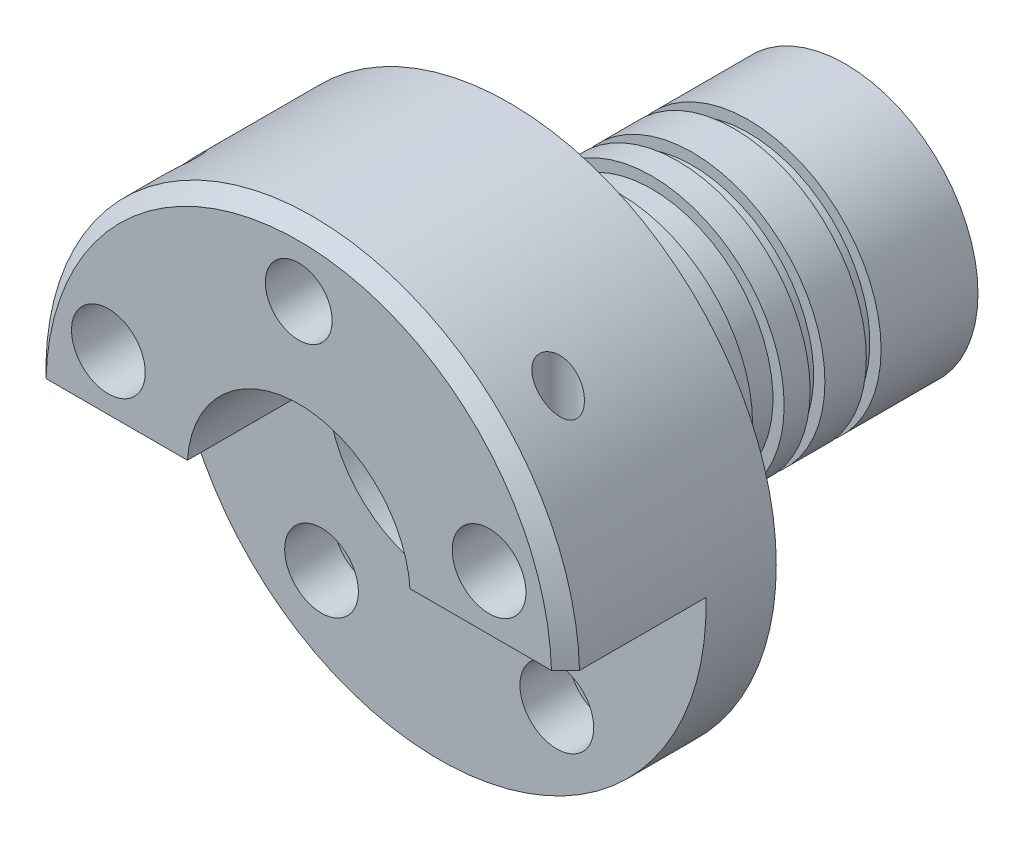
SolidWorks part; units mm, degrees
ref_plane "Front Plane" through (0, 0, 0) normal (0, 0, 1) x (1, 0, 0)
ref_plane "Top Plane" through (0, 0, 0) normal (0, 1, 0) x (1, 0, 0)
ref_plane "Right Plane" through (0, 0, 0) normal (1, 0, 0) x (0, 0, -1)
sketch "Sketch1" plane through (0, 0, 0) normal (0, 0, 1) x (1, 0, 0)
  circle A0 centre (0, 0) radius 15.875
  circle A1 centre (0, 0) radius 18.875
  dimension "D1" = 31.75
  dimension "D2" = 37.75
extrude "Boss-Extrude1" add sketch "Sketch1" along normal blind 47.85
sketch "Sketch2" plane through (0, 0, 47.85) normal (0, 0, 1) x (1, 0, 0)
  circle A0 centre (0, 0) radius 38
  dimension "D1" = 76
extrude "Boss-Extrude2" add sketch "Sketch2" along normal blind 30
sketch "Sketch3" plane through (0, 0, 47.85) normal (0, 0, -1) x (-1, 0, 0)
  circle A0 centre (0, 0) radius 15.875
  circle A1 centre (0, 0) radius 15.875 construction
extrude "Cut-Extrude1" cut sketch "Sketch3" against normal blind 47.85
sketch "Sketch4" plane through (0, 0, 0) normal (0, 1, 0) x (1, 0, 0)
  line L0 (-38, -57.85) -> (38, -57.85) construction
  line L1 (-38, -47.85) -> (-38, -77.85) construction
  line L2 (38, -77.85) -> (38, -47.85) construction
  line L3 (38, -47.85) -> (-38, -47.85) construction
  line L4 (-38, -77.85) -> (38, -77.85) construction
  line L5 (-38, -57.85) -> (38, -57.85)
  line L6 (-38, -57.85) -> (-38, -77.85)
  line L7 (-38, -77.85) -> (38, -77.85)
  line L8 (38, -57.85) -> (38, -77.85)
  dimension "D1" = 10
extrude "Cut-Extrude2" cut sketch "Sketch4" against normal blind 47.85
sketch "Sketch5" plane through (0, 0, 0) normal (0, -1, 0) x (-1, 0, 0)
  line L0 (38, -77.85) -> (15.875, -57.85) construction
  line L1 (-15.875, -77.85) -> (-38, -57.85) construction
  circle A0 centre (26.9375, -67.85) radius 2.65
  circle A1 centre (-26.9375, -67.85) radius 2.65
  dimension "D1" = 5.3
  dimension "D2" = 5.3
extrude "Cut-Extrude3" cut sketch "Sketch5" against normal blind 47.85
sketch "Sketch11" plane through (0, 0, 77.85) normal (0, 0, 1) x (1, 0, 0)
  line L0 (0, 0) -> (0, 38) construction
  arc A0 (38, 0) -> (-38, 0) centre (0, 0) ccw construction
  circle A1 centre (0, 0) radius 28.5 construction
  circle A2 centre (0, 28.5) radius 1
  point P19 (0, 0)
  dimension "D1" = 57
  dimension "D2" = 2
extrude "Cut-Extrude4" cut sketch "Sketch11" against normal up to surface (30 mm away) up to face at (18.875, 0, 47.85)
sketch "Sketch12" plane through (0, 0, 77.85) normal (0, 0, 1) x (1, 0, 0)
  circle A0 centre (0, 28.5) radius 4.7625
  point P16 (0, 0)
  dimension "D1" = 9.525
extrude "Cut-Extrude5" cut sketch "Sketch12" against normal blind 8
sketch "Sketch13" plane through (0, 0, 0) normal (1, 0, 0) x (0, 0, -1)
  line L0 (0, 0) -> (-47.85, 0) construction
  line L1 (0, -18.875) -> (0, 18.875) construction
  line L2 (-47.85, -38) -> (-47.85, 38) construction
  line L3 (-14.85, 0) -> (-14.85, 18.875) construction
  line L4 (0, 18.875) -> (-47.85, 18.875) construction
  line L5 (-22.85, 0) -> (-22.85, 18.875) construction
  line L6 (-35.85, 0) -> (-35.85, 18.875) construction
  line L7 (-39.85, 0) -> (-39.85, 18.875) construction
  line L8 (-47.85, -18.875) -> (-47.85, 18.875) construction
  line L10 (-29.85, 18.375) -> (-29.85, 0) construction
  line L11 (-47.85, -18.875) -> (0, -18.875) construction
  line L12 (-15.9, 17.275) -> (-47.85, 17.275) construction
  line L13 (-15.9, 20.475) -> (-13.8, 20.475)
  line L14 (-15.9, 20.475) -> (-15.9, 17.275)
  line L15 (-15.9, 17.275) -> (-13.8, 17.275)
  line L16 (-13.8, 20.475) -> (-13.8, 17.275)
  line L17 (-15.9, 20.475) -> (-13.8, 17.275) construction
  line L18 (-15.9, 17.275) -> (-13.8, 20.475) construction
  line L19 (0, 0) -> (0, 17.875) construction
  line L20 (-23.9, 20.475) -> (-21.8, 20.475)
  line L21 (-23.9, 20.475) -> (-23.9, 17.275)
  line L22 (-23.9, 17.275) -> (-21.8, 17.275)
  line L23 (-21.8, 20.475) -> (-21.8, 17.275)
  line L24 (-23.9, 20.475) -> (-21.8, 17.275) construction
  line L25 (-23.9, 17.275) -> (-21.8, 20.475) construction
  line L26 (-36.9, 20.475) -> (-34.8, 20.475)
  line L27 (-36.9, 20.475) -> (-36.9, 17.275)
  line L28 (-36.9, 17.275) -> (-34.8, 17.275)
  line L29 (-34.8, 20.475) -> (-34.8, 17.275)
  line L30 (-36.9, 20.475) -> (-34.8, 17.275) construction
  line L31 (-36.9, 17.275) -> (-34.8, 20.475) construction
  line L32 (-40.9, 20.475) -> (-38.8, 20.475)
  line L33 (-40.9, 20.475) -> (-40.9, 17.275)
  line L34 (-40.9, 17.275) -> (-38.8, 17.275)
  line L35 (-38.8, 20.475) -> (-38.8, 17.275)
  line L36 (-40.9, 20.475) -> (-38.8, 17.275) construction
  line L37 (-40.9, 17.275) -> (-38.8, 20.475) construction
  line L38 (-16.9262, 17.275) -> (-16.9262, 19.275) construction
  line L40 (-32.1, 19.475) -> (-27.6, 19.475)
  line L41 (-32.1, 19.475) -> (-32.1, 17.275)
  line L42 (-32.1, 17.275) -> (-27.6, 17.275)
  line L43 (-27.6, 19.475) -> (-27.6, 17.275)
  line L44 (-32.1, 19.475) -> (-27.6, 17.275) construction
  line L45 (-32.1, 17.275) -> (-27.6, 19.475) construction
  point P21 (-29.85, 9.1875)
  dimension "D1" = 8
  dimension "D2" = 12
  dimension "D3" = 25
  dimension "D4" = 33
  dimension "D5" = 1.6
  dimension "D6" = 2.1
  dimension "D7" = 2.1
  dimension "D8" = 2.1
  dimension "D9" = 2.1
  dimension "D10" = 2
  dimension "D11" = 4.5
  dimension "D12" = 18
revolve "Cut-Revolve1" cut sketch "Sketch13" angle 360 about L0
sketch "Sketch18" plane through (0, 0, 77.85) normal (0, 0, 1) x (1, 0, 0)
  circle A0 centre (0, 28.5) radius 3.125 construction
  circle A1 centre (27.1051, 8.807) radius 3.125
  circle A2 centre (16.7519, -23.057) radius 3.125
  circle A3 centre (-16.7519, -23.057) radius 3.125
  circle A4 centre (-27.1051, 8.807) radius 3.125
  point P13 (0, 0)
  dimension "D1" = 6.25
  dimension "D2" = 5
extrude "Cut-Extrude8" cut sketch "Sketch18" against normal up to surface (30 mm away) up to face at (1, 28.5, 47.85)
sketch "Sketch19" plane through (0, 0, 77.85) normal (0, 0, 1) x (1, 0, 0)
  circle A0 centre (0, 28.5) radius 5.25 construction
  circle A1 centre (27.1051, 8.807) radius 5.25
  circle A2 centre (16.7519, -23.057) radius 5.25
  circle A3 centre (-16.7519, -23.057) radius 5.25
  circle A4 centre (-27.1051, 8.807) radius 5.25
  point P13 (0, 0)
  dimension "D1" = 10.5
  dimension "D2" = 5
extrude "Cut-Extrude9" cut sketch "Sketch19" against normal blind 27
ref_plane "Plane4" through (0, 38, 0) normal (0, 1, 0) x (1, 0, 0)
sketch "Sketch27" plane through (0, 0, 47.85) normal (0, 0, -1) x (-1, 0, 0)
  line L0 (0, 33.125) -> (0, 34.725) construction
  circle A0 centre (0, 28.5) radius 4.625 construction
  circle A1 centre (0, 28.5) radius 6.225
  dimension "D1" = 9.25
  dimension "D2" = 1.6
extrude "Cut-Extrude12" cut sketch "Sketch27" against normal blind 1.6
chamfer "Chamfer1" distance 2 angle 45 1 edges at (0, 38, 77.85)
sketch "Sketch28" plane through (0, 0, 0) normal (0, -1, 0) x (-1, 0, 0)
  line L0 (-15.875, -77.85) -> (15.875, -77.85) construction
  line L1 (38, -57.85) -> (-38, -57.85)
  line L2 (38, -57.85) -> (38, -77.85)
  line L3 (38, -77.85) -> (-38, -77.85)
  line L4 (-38, -57.85) -> (-38, -77.85)
  line L5 (-38, -75.85) -> (-38, -57.85) construction
extrude "Cut-Extrude13" cut sketch "Sketch28" against normal blind 1
